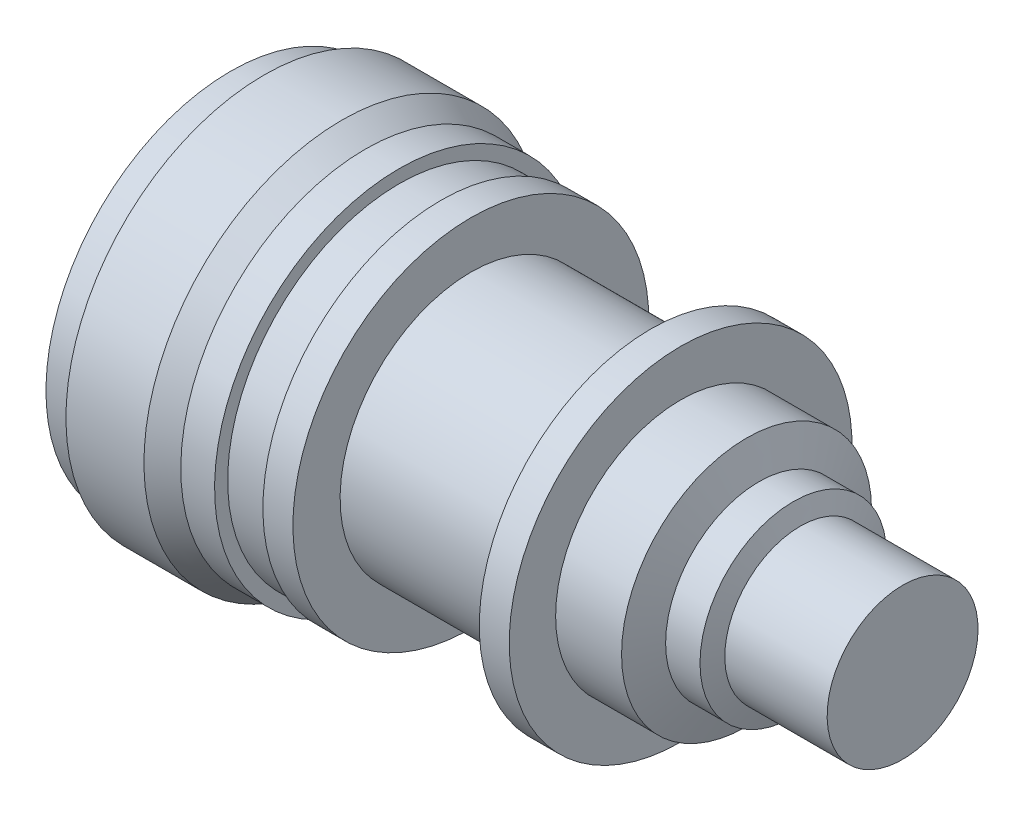
SolidWorks part; units mm, degrees
ref_plane "Front Plane" through (0, 0, 0) normal (0, 0, 1) x (1, 0, 0)
ref_plane "Top Plane" through (0, 0, 0) normal (0, 1, 0) x (1, 0, 0)
ref_plane "Right Plane" through (0, 0, 0) normal (1, 0, 0) x (0, 0, -1)
sketch "Sketch1" plane through (0, 0, 0) normal (0, 0, 1) x (1, 0, 0)
  line L0 (182.8158, 101.1674) -> (227.8158, 101.1674) construction
  dimension "D1" = 45
sketch "Sketch2" plane through (0, 0, 0) normal (0, 0, 1) x (1, 0, 0)
  line L0 (241.708, 102.7418) -> (182.0216, 102.7418) construction
  line L1 (187.7276, 102.7418) -> (187.7276, 114.0287)
  line L12 (202.4342, 110.7418) -> (213.4342, 110.7418)
  line L13 (213.4342, 110.7418) -> (213.4342, 113.2278)
  line L14 (213.4342, 113.2278) -> (215.2657, 113.2278)
  line L15 (215.2657, 113.2278) -> (215.2657, 110.3889)
  line L16 (215.2657, 110.3889) -> (219.2991, 110.3889)
  line L17 (219.2991, 110.3889) -> (220.055, 108.4497)
  line L18 (220.055, 108.4497) -> (222.1585, 108.4497)
  line L19 (222.1585, 108.4497) -> (222.5843, 107.3576)
  line L20 (222.5843, 107.3576) -> (228.8436, 107.3576)
  line L21 (228.8436, 107.3576) -> (228.8436, 102.7418)
  line L25 (187.7276, 102.7418) -> (228.8436, 102.7418)
  line L26 (187.7276, 114.0287) -> (189.7754, 114.0287)
  line L27 (189.7754, 114.0287) -> (189.7754, 114.855)
  line L28 (189.7754, 114.855) -> (194.5479, 114.855)
  line L29 (194.5479, 114.855) -> (195.9759, 114.0287)
  line L30 (195.9759, 114.0287) -> (198.0427, 114.0287)
  line L31 (198.0427, 114.0287) -> (198.0427, 113.2278)
  line L32 (198.0427, 113.2278) -> (200.598, 113.2278)
  line L33 (200.598, 113.2278) -> (200.598, 113.6282)
  line L34 (200.598, 113.6282) -> (202.4342, 113.6282)
  line L35 (202.4342, 113.6282) -> (202.4342, 110.7418)
  dimension "D1" = 11
  dimension "D2" = 4.0333
  dimension "D3" = 8
revolve "Revolve2" add sketch "Sketch2" angle 360 about L0
